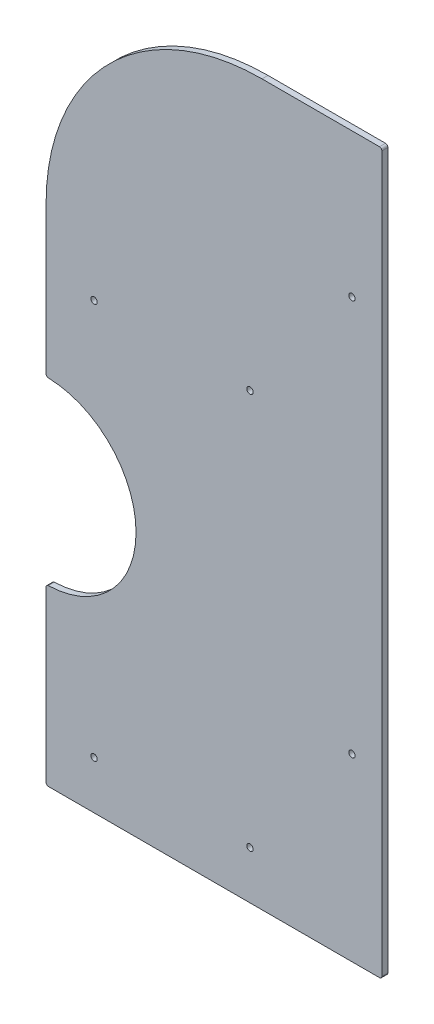
SolidWorks part; units mm, degrees
material "PE High Density"
ref_plane "Front Plane" through (0, 0, 0) normal (0, 0, 1) x (1, 0, 0)
ref_plane "Top Plane" through (0, 0, 0) normal (0, 1, 0) x (1, 0, 0)
ref_plane "Right Plane" through (0, 0, 0) normal (1, 0, 0) x (0, 0, -1)
sketch "Sketch1" plane through (0, 0, 0) normal (0, 0, 1) x (1, 0, 0)
  line L1 (-177.8, 381) -> (177.8, 381)
  line L2 (-177.8, 381) -> (-177.8, -381)
  line L3 (-177.8, -381) -> (177.8, -381)
  line L4 (177.8, 381) -> (177.8, -381)
  line L5 (-177.8, 381) -> (177.8, -381) construction
  line L6 (-177.8, -381) -> (177.8, 381) construction
  point P0 (0, 0)
  dimension "D1" = 762
  dimension "D2" = 355.6
extrude "Boss-Extrude1" add sketch "Sketch1" along normal blind 6.35
sketch "Sketch2" plane through (0, 0, 6.35) normal (0, 0, 1) x (1, 0, 0)
  line L0 (-177.8, -381) -> (177.8, -381) construction
  line L1 (-177.8, -381) -> (177.8, -381) construction
  line L3 (177.8, 381) -> (-177.8, 381) construction
  line L5 (-177.8, 381) -> (-177.8, -381) construction
  line L6 (177.8, 381) -> (177.8, -381) construction
  circle A0 centre (-127, -330.2) radius 16.7005
  circle A1 centre (146.05, -190.5) radius 16.7005
  circle A2 centre (-127, 88.9) radius 16.7005
  circle A3 centre (146.05, 228.6) radius 16.7005
  circle A4 centre (38.1, 88.9) radius 16.7005
  circle A5 centre (38.1, -330.2) radius 16.7005
  circle A6 centre (146.05, 228.6) radius 3.3734
  circle A7 centre (38.1, 88.9) radius 3.3734
  circle A8 centre (-127, 88.9) radius 3.3734
  circle A9 centre (146.05, -190.5) radius 3.3734
  circle A10 centre (38.1, -330.2) radius 3.3734
  circle A11 centre (-127, -330.2) radius 3.3734
  dimension "D3" = 33.401
  dimension "D6" = 33.401
  dimension "D8" = 33.401
  dimension "D12" = 33.401
  dimension "D13" = 33.401
  dimension "D17" = 33.401
  dimension "D16" = 6.7469
  dimension "D18" = 6.7469
  dimension "D19" = 6.7469
  dimension "D20" = 6.7469
  dimension "D21" = 6.7469
  dimension "D22" = 6.7469
  dimension "D1" = 50.8
  dimension "D2" = 469.9
  dimension "D4" = 50.8
  dimension "D5" = 31.75
  dimension "D7" = 152.4
  dimension "D9" = 50.8
  dimension "D10" = 190.5
  dimension "D11" = 31.75
  dimension "D14" = 165.1
  dimension "D15" = 165.1
fillet "Fillet1" radius 228.6 1 edges at (-177.8, 381, 3.175)
sketch "Sketch3" plane through (0, 0, 6.35) normal (0, 0, 1) x (1, 0, 0)
  line L0 (-177.8, 381) -> (-177.8, -381) construction
  circle A0 centre (-177.8, -101.6) radius 95.25
  dimension "D1" = 190.5
  dimension "D2" = 101.6
extrude "Cut-Extrude1" cut sketch "Sketch3" against normal through all
extrude "Cut-Extrude2" cut sketch "Sketch2" against normal through all contours A6 | A7 | A8 | A9 | A10 | A11
fillet "Fillet2" radius 2.54 5 edges at (-177.8, -196.85, 3.175) (-177.8, -6.35, 3.175) (-177.8, -381, 3.175) (177.8, -381, 3.175) (177.8, 381, 3.175)
